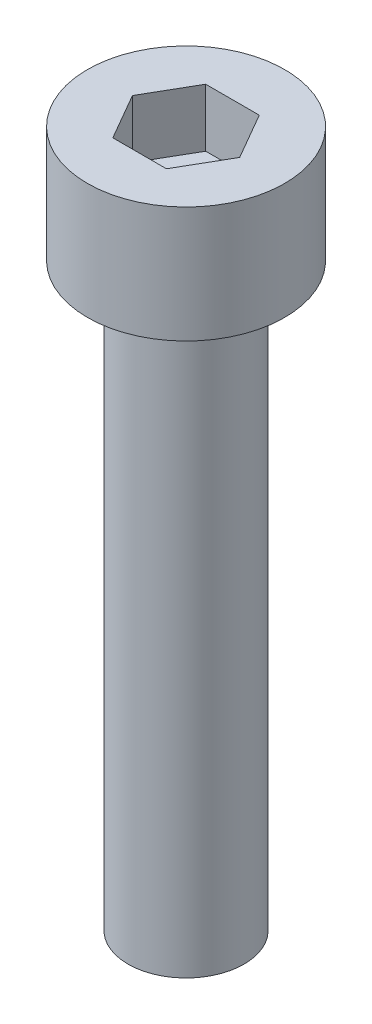
SolidWorks part; units mm, degrees
ref_plane "Płaszczyzna przednia" through (0, 0, 0) normal (0, 0, 1) x (1, 0, 0)
ref_plane "Płaszczyzna górna" through (0, 0, 0) normal (0, 1, 0) x (1, 0, 0)
ref_plane "Płaszczyzna prawa" through (0, 0, 0) normal (1, 0, 0) x (0, 0, -1)
sketch "Sketch1" plane through (0, 0, 0) normal (0, 0, 1) x (1, 0, 0)
  line L0 (0, 0) -> (2.5, 0)
  line L1 (2.5, 0) -> (2.5, 25)
  line L2 (2.5, 25) -> (4.25, 25)
  line L3 (4.25, 25) -> (4.25, 30)
  line L4 (4.25, 30) -> (0, 30)
  line L5 (0, 30) -> (0, 0)
  dimension "D1" = 2.5
  dimension "D2" = 25
  dimension "D3" = 5
  dimension "D4" = 4.25
revolve "Revolve1" add sketch "Sketch1" angle 360 about L5
sketch "Sketch2" plane through (0, 30, 0) normal (0, 1, 0) x (1, 0, 0)
  line L1 (1.1547, 2) -> (-1.1547, 2)
  line L2 (-1.1547, 2) -> (-2.3094, 0)
  line L3 (-2.3094, 0) -> (-1.1547, -2)
  line L4 (-1.1547, -2) -> (1.1547, -2)
  line L5 (1.1547, -2) -> (2.3094, 0)
  line L6 (2.3094, 0) -> (1.1547, 2)
  circle A0 centre (0, 0) radius 2 construction
  dimension "D1" = 4
extrude "Cut-Extrude1" cut sketch "Sketch2" against normal blind 2.5
